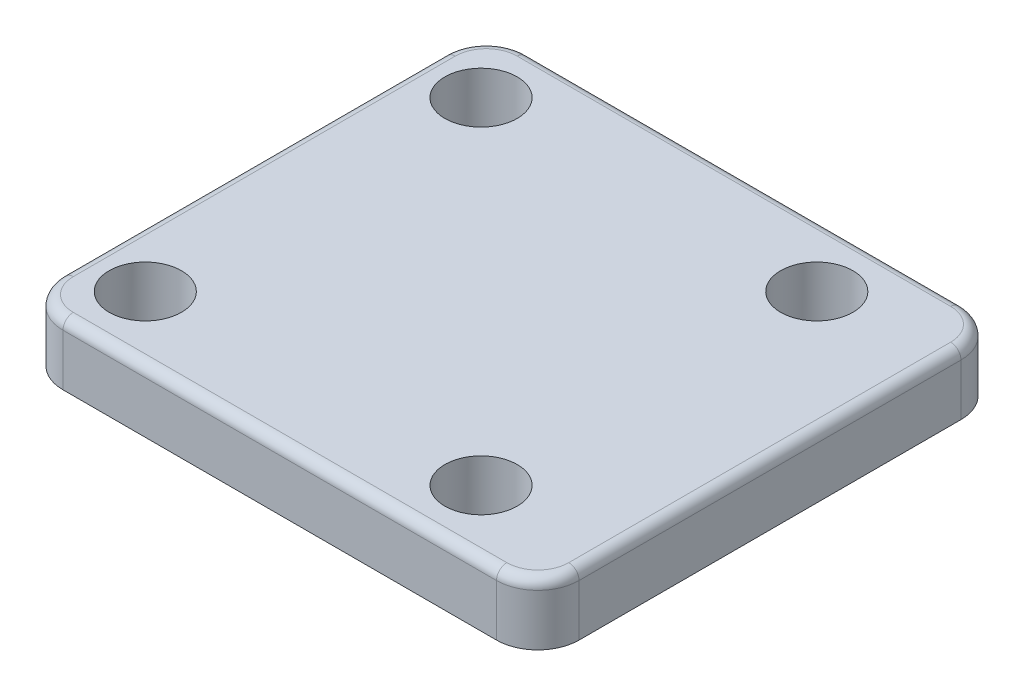
SolidWorks part; units mm, degrees
material "Commercially Pure Grade 2 Textured (SS)"
ref_plane "Front Plane" through (0, 0, 0) normal (0, 0, 1) x (1, 0, 0)
ref_plane "Top Plane" through (0, 0, 0) normal (0, 1, 0) x (1, 0, 0)
ref_plane "Right Plane" through (0, 0, 0) normal (1, 0, 0) x (0, 0, -1)
sketch "Sketch1" plane through (0, 0, 0) normal (0, 1, 0) x (1, 0, 0)
  line L1 (-18, 22.5) -> (24, 22.5)
  line L2 (-22, 18.5) -> (-22, -18.5)
  line L3 (-18, -22.5) -> (24, -22.5)
  line L4 (28, 18.5) -> (28, -18.5)
  arc A0 (24, 22.5) -> (28, 18.5) centre (24, 18.5) cw
  arc A1 (-22, -18.5) -> (-18, -22.5) centre (-18, -18.5) ccw
  arc A2 (24, -22.5) -> (28, -18.5) centre (24, -18.5) ccw
  arc A3 (-18, 22.5) -> (-22, 18.5) centre (-18, 18.5) ccw
  point P7 (28, 22.5)
  point P12 (28, -22.5)
  point P15 (-22, 22.5)
  dimension "D5" = 4
  dimension "D1" = 50
  dimension "D2" = 45
  dimension "D3" = 22
  dimension "D4" = 22.5
extrude "Boss-Extrude1" add sketch "Sketch1" along normal blind 6
fillet "Fillet1" radius 1 8 edges at (28, 6, 0) (26.8284, 6, 21.3284) (3, 6, 22.5) (-20.8284, 6, 21.3284) (-22, 6, 0) (-20.8284, 6, -21.3284) (3, 6, -22.5) (26.8284, 6, -21.3284)
sketch "Sketch2" plane through (0, 0, 0) normal (0, -1, 0) x (1, 0, 0)
  circle A0 centre (0, 0) radius 16
  dimension "D1" = 32
extrude "Boss-Extrude2" add sketch "Sketch2" along normal blind 2
sketch "Sketch3" plane through (0, 6, 0) normal (0, 1, 0) x (1, 0, 0)
  line L0 (-23, 0) -> (0, 0) construction
  line L1 (0, 0) -> (-16.2635, 16.2635) construction
  circle A0 centre (0, 0) radius 23 construction
  circle A1 centre (-16.2635, 16.2635) radius 3.5
  circle A2 centre (16.2635, 16.2635) radius 3.5
  circle A3 centre (16.2635, -16.2635) radius 3.5
  circle A4 centre (-16.2635, -16.2635) radius 3.5
  point P15 (0, 0)
  dimension "D1" = 46
  dimension "D3" = 7
  dimension "D2" = 45
  dimension "D4" = 4
extrude "Cut-Extrude1" cut sketch "Sketch3" against normal through all
chamfer "Chamfer1" distance 1 angle 60 1 edges at (0, -2, -16)
